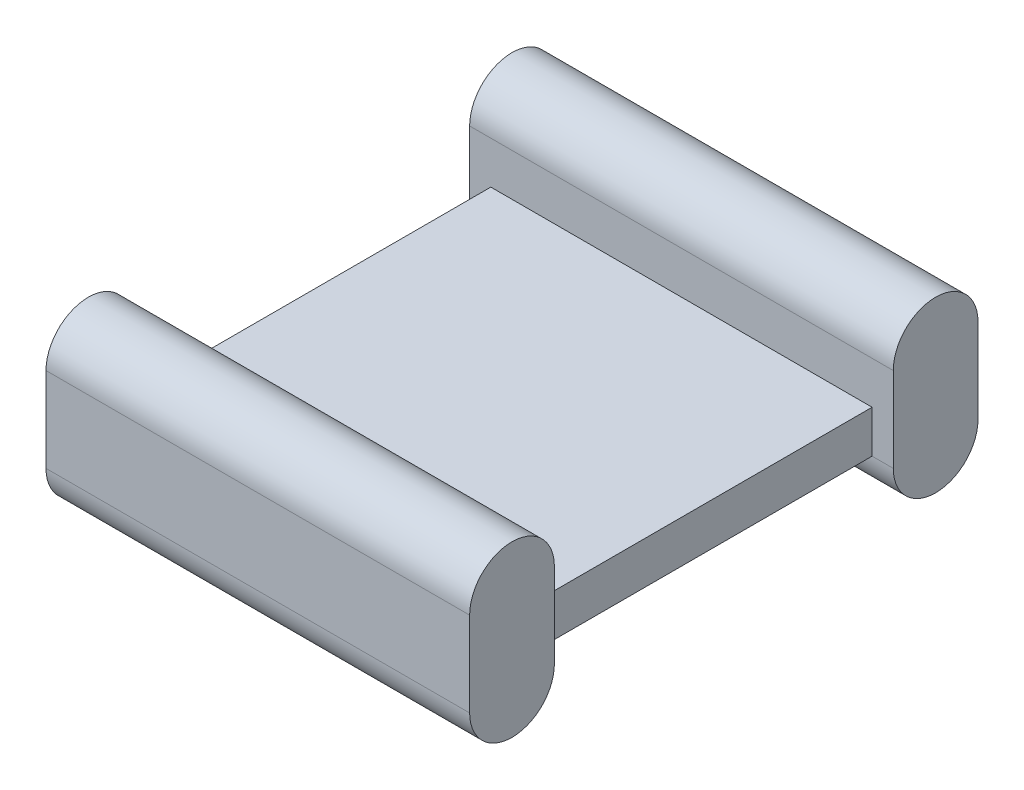
SolidWorks part; units mm, degrees
material "Plain Carbon Steel"
ref_plane "Front Plane" through (0, 0, 0) normal (0, 0, 1) x (1, 0, 0)
ref_plane "Top Plane" through (0, 0, 0) normal (0, 1, 0) x (1, 0, 0)
ref_plane "Right Plane" through (0, 0, 0) normal (1, 0, 0) x (0, 0, -1)
sketch "Sketch1" plane through (0, 0, 0) normal (0, 1, 0) x (1, 0, 0)
  line L1 (114.3, -152.4) -> (-114.3, -152.4)
  line L2 (114.3, -152.4) -> (114.3, 152.4)
  line L3 (114.3, 152.4) -> (-114.3, 152.4)
  line L4 (-114.3, -152.4) -> (-114.3, 152.4)
  line L5 (114.3, -152.4) -> (-114.3, 152.4) construction
  line L6 (114.3, 152.4) -> (-114.3, -152.4) construction
  point P0 (0, 0)
  dimension "D1" = 304.8
  dimension "D2" = 228.6
extrude "Boss-Extrude1" add sketch "Sketch1" along normal mid plane 25.4
sketch "Sketch2" plane through (0, 0, 0) normal (1, 0, 0) x (0, 0, -1)
  line L0 (-127, -12.7) -> (-127, 38.1) construction
  line L1 (-152.4, 12.7) -> (152.4, 12.7) construction
  line L2 (-152.4, -12.7) -> (-152.4, 38.1)
  line L3 (-101.6, -12.7) -> (-101.6, 38.1)
  line L4 (0, 55.88) -> (0, -55.88) construction
  line L5 (127, -12.7) -> (127, 38.1) construction
  line L6 (101.6, -12.7) -> (101.6, 38.1)
  line L7 (152.4, -12.7) -> (152.4, 38.1)
  arc A0 (-152.4, -12.7) -> (-101.6, -12.7) centre (-127, -12.7) ccw
  arc A1 (-101.6, 38.1) -> (-152.4, 38.1) centre (-127, 38.1) ccw
  arc A2 (101.6, -12.7) -> (152.4, -12.7) centre (127, -12.7) ccw
  arc A3 (152.4, 38.1) -> (101.6, 38.1) centre (127, 38.1) ccw
  point P4 (-127, 12.7)
  point P13 (127, 12.7)
  dimension "D1" = 50.8
  dimension "D2" = 101.6
  dimension "D3" = 127
  dimension "D4" = 127
extrude "Boss-Extrude2" add sketch "Sketch2" along normal mid plane 254
